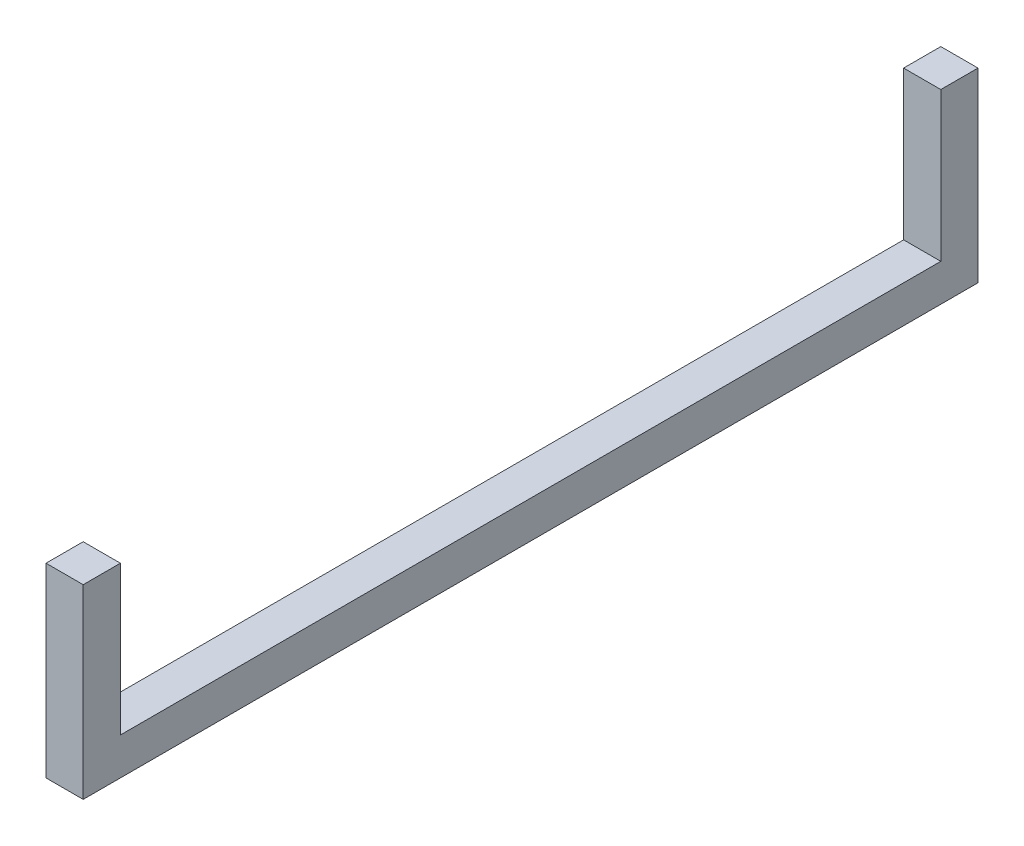
SolidWorks part; units mm, degrees
ref_plane "Plan de face" through (0, 0, 0) normal (0, 0, 1) x (1, 0, 0)
ref_plane "Plan de dessus" through (0, 0, 0) normal (0, 1, 0) x (1, 0, 0)
ref_plane "Plan de droite" through (0, 0, 0) normal (1, 0, 0) x (0, 0, -1)
sketch "Esquisse1" plane through (0, 0, 0) normal (0, 0, 1) x (1, 0, 0)
  line L0 (0, 5.0593) -> (0, -7.5) construction
  line L1 (-2.5, 2.5) -> (2.5, 2.5)
  line L2 (-2.5, 2.5) -> (-2.5, -2.5)
  line L3 (-2.5, -2.5) -> (2.5, -2.5)
  line L4 (2.5, 2.5) -> (2.5, -2.5)
  line L5 (-9.4588, 0) -> (9.2022, 0) construction
  dimension "D1" = 5
  dimension "D2" = 5
extrude "Boss.-Extru.1" add sketch "Esquisse1" along normal blind 120.28
sketch "Esquisse3" plane through (0, 2.5, 0) normal (0, 1, 0) x (1, 0, 0)
  line L0 (-2.5, 0) -> (2.5, 0)
  line L1 (2.5, 0) -> (2.5, -5)
  line L2 (2.5, -120.28) -> (2.5, 0) construction
  line L3 (2.5, -5) -> (-2.5, -5)
  line L4 (-2.5, -120.28) -> (-2.5, 0) construction
  line L5 (-2.5, -5) -> (-2.5, 0)
  line L6 (-2.5, -120.28) -> (-2.5, -115.28)
  line L7 (-2.5, -115.28) -> (2.5, -115.28)
  line L8 (2.5, -115.28) -> (2.5, -120.28)
  line L9 (2.5, -120.28) -> (-2.5, -120.28)
  dimension "D1" = 5
  dimension "D2" = 5
extrude "Boss.-Extru.2" add sketch "Esquisse3" along normal blind 20
